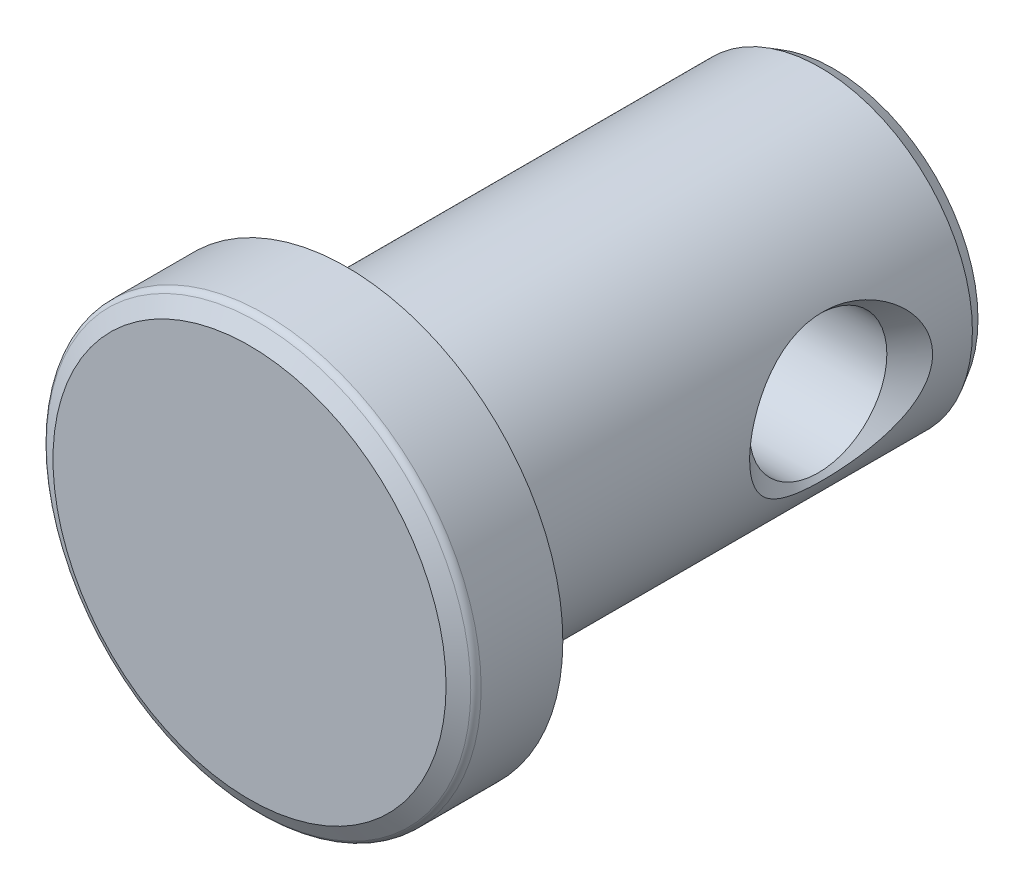
SolidWorks part; units mm, degrees
ref_plane "Front" through (0, 0, 0) normal (0, 0, 1) x (1, 0, 0)
ref_plane "Top" through (0, 0, 0) normal (0, 1, 0) x (1, 0, 0)
ref_plane "Right" through (0, 0, 0) normal (1, 0, 0) x (0, 0, -1)
sketch "Sketch1" plane through (0, 0, 0) normal (1, 0, 0) x (0, 0, -1)
  line L0 (-8.89, 0) -> (-6.35, 0) construction
  line L1 (-6.35, 0) -> (6.35, 0) construction
  line L2 (-8.89, 0) -> (-8.89, 5.1308)
  line L3 (-8.89, 5.1308) -> (-8.5967, 5.6388)
  line L4 (-8.5967, 5.6388) -> (-6.35, 5.6388)
  line L5 (-6.35, 5.6388) -> (-6.35, 3.9751)
  line L6 (-6.35, 3.9751) -> (6.0057, 3.9751)
  line L7 (6.0057, 3.9751) -> (6.35, 3.7763)
  line L8 (6.35, 3.7763) -> (6.35, 0)
  line L9 (-6.35, -3.9751) -> (-6.35, -5.6388)
  circle A0 centre (2.5781, 0) radius 1.7907
  point P4 (0, 0)
  point P17 (0.7874, 0)
  dimension "Through Hole Diameter" = 3.5814
  dimension "Diameter" = 7.9502
  dimension "D1" = 30
  dimension "D2" = 0.1988
  dimension "Head Height" = 2.54
  dimension "Head Diameter" = 11.2776
  dimension "D5" = 0.508
  dimension "Length" = 12.7
  dimension "Usable Length" = 7.1374
sketch "Sketch2" plane through (0, 0, 0) normal (1, 0, 0) x (0, 0, -1)
  line L0 (6.35, 3.7763) -> (6.35, 0) construction
  line L1 (6.0057, 3.9751) -> (6.35, 3.7763) construction
  line L2 (-6.35, 3.9751) -> (6.0057, 3.9751) construction
  line L3 (-6.35, 5.6388) -> (-6.35, 3.9751) construction
  line L4 (-8.5967, 5.6388) -> (-6.35, 5.6388) construction
  line L5 (-8.89, 5.1308) -> (-8.5967, 5.6388) construction
  line L6 (-8.89, 0) -> (-8.89, 5.1308) construction
  line L7 (6.35, 3.7763) -> (6.35, 0)
  line L8 (6.0057, 3.9751) -> (6.35, 3.7763)
  line L9 (-6.35, 3.9751) -> (6.0057, 3.9751)
  line L10 (-6.35, 5.6388) -> (-6.35, 3.9751)
  line L11 (-8.5967, 5.6388) -> (-6.35, 5.6388)
  line L12 (-8.89, 5.1308) -> (-8.5967, 5.6388)
  line L13 (-8.89, 0) -> (-8.89, 5.1308)
  line L14 (-8.89, 0) -> (6.35, 0)
revolve "Revolve1" add sketch "Sketch2" angle 360 about L1
sketch "Sketch3" plane through (0, 0, 0) normal (1, 0, 0) x (0, 0, -1)
  circle A0 centre (2.5781, 0) radius 1.7907 construction
  circle A1 centre (2.5781, 0) radius 1.7907
extrude "Cut-Extrude1" cut sketch "Sketch3" against normal through all both and the other way through all
fillet "Fillet1" radius 0.1988 2 edges at (3.9751, 0, 6.35) (5.6388, 0, 8.5967)
sketch "Sketch4" plane through (0, 0, 0) normal (0, 1, 0) x (1, 0, 0)
  line L0 (3.9751, 2.5781) -> (-3.9751, 2.5781) construction
  line L1 (3.9751, 2.5781) -> (3.9751, 0.1905)
  line L2 (3.9751, 0.1905) -> (1.5875, 2.5781)
  line L3 (3.9751, -6.1512) -> (3.9751, 0.7874) construction
  line L4 (0, 2.5781) -> (0, 0) construction
  line L5 (-3.9751, 0.1905) -> (-1.5875, 2.5781)
  line L6 (-3.9751, 2.5781) -> (-3.9751, 0.1905)
  line L7 (-3.9751, 2.5781) -> (-1.5875, 2.5781)
  line L8 (1.5875, 2.5781) -> (3.9751, 2.5781)
  dimension "D1" = 45
  dimension "D2" = 4.7752
revolve "Cut-Revolve1" cut sketch "Sketch4" angle 360 about L0
equation "\"D2@Sketch1\"=\"Diameter@Sketch1\" * .025"
equation "\"D5@Sketch1\" = \"Head Height@Sketch1\" * .2"
equation "\"D1@Fillet1\"=\"D2@Sketch1\""
equation "\"D2@Sketch4\"=\"Through Hole Diameter@Sketch1\" * 4/3"
